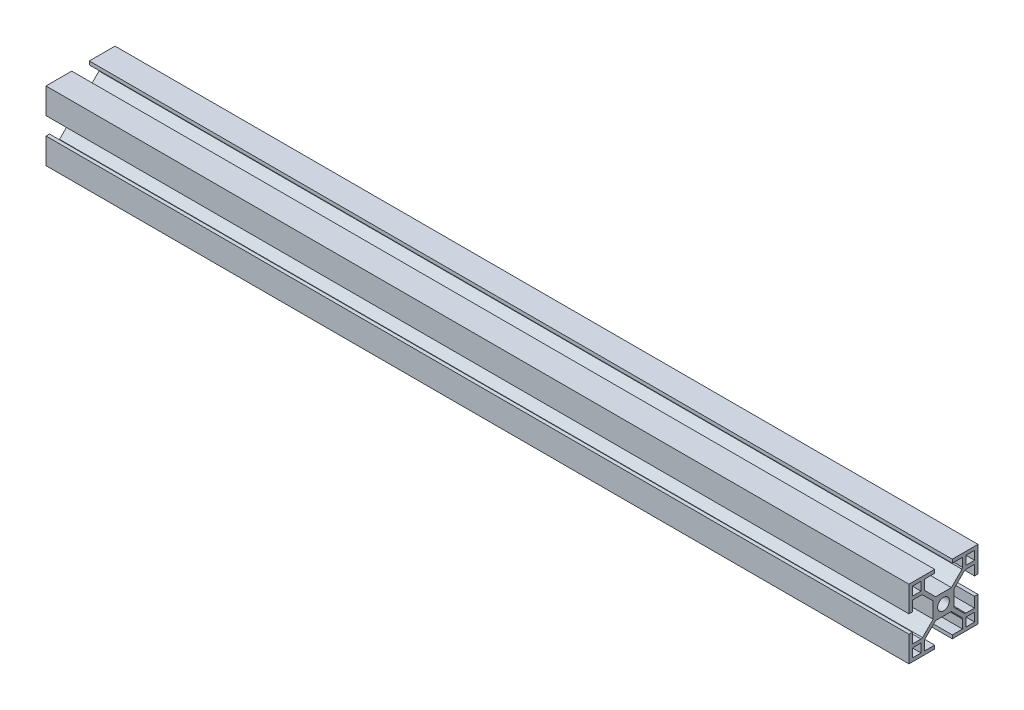
SolidWorks part; units mm, degrees
ref_plane "前视基准面" through (0, 0, 0) normal (0, 0, 1) x (1, 0, 0)
ref_plane "上视基准面" through (0, 0, 0) normal (0, 1, 0) x (1, 0, 0)
ref_plane "右视基准面" through (0, 0, 0) normal (1, 0, 0) x (0, 0, -1)
sketch "草图1" plane through (0, 0, 0) normal (1, 0, 0) x (0, 0, -1)
  line L0 (0, 0) -> (0, 6) construction
  line L5 (0, 6) -> (4.5858, 6)
  line L6 (6, 0) -> (6, -4.5858)
  line L10 (12.133, -10.7188) -> (6, -4.5858)
  line L11 (10.7188, 12.133) -> (4.5858, 6)
  line L12 (20, 20) -> (20, 5.1)
  line L18 (20, -20) -> (5.1, -20)
  line L22 (12.133, -10.7188) -> (13, -11)
  line L23 (18, -13) -> (18, -18)
  line L24 (18, -15.5) -> (18, -13)
  line L28 (18, -13) -> (13, -13)
  line L32 (13, -13) -> (13, -18)
  line L33 (18, -18) -> (13, -18)
  line L34 (11, -13) -> (11, -18)
  line L38 (11, -18) -> (5.1, -18)
  line L42 (10.7188, -12.133) -> (11, -13)
  line L43 (10.7188, -12.133) -> (4.5858, -6)
  line L44 (4.5858, -6) -> (0, -6)
  line L45 (10.7188, 12.133) -> (11, 13)
  line L46 (5.1, -18) -> (5.1, -20)
  line L47 (13, 18) -> (18, 18)
  line L49 (15.5, 18) -> (13, 18)
  line L56 (13, 18) -> (13, 13)
  line L59 (13, 13) -> (18, 13)
  line L60 (18, 18) -> (18, 13)
  line L61 (13, 11) -> (18, 11)
  line L62 (18, 11) -> (18, 5.1)
  line L63 (12.133, 10.7188) -> (13, 11)
  line L64 (12.133, 10.7188) -> (6, 4.5858)
  line L65 (6, 4.5858) -> (6, 0)
  line L66 (18, 5.1) -> (20, 5.1)
  line L67 (11, 18) -> (5.1, 18)
  line L68 (11, 13) -> (11, 18)
  line L69 (5.1, 18) -> (5.1, 20)
  line L70 (20, 20) -> (5.1, 20)
  line L71 (18, -11) -> (18, -5.1)
  line L72 (13, -11) -> (18, -11)
  line L73 (18, -5.1) -> (20, -5.1)
  line L74 (20, -20) -> (20, -5.1)
  line L75 (0, 0) -> (6, 0) construction
  line L76 (0, -6) -> (-4.5858, -6)
  line L77 (-10.7188, -12.133) -> (-4.5858, -6)
  line L78 (-20, -20) -> (-20, -5.1)
  line L79 (-10.7188, -12.133) -> (-11, -13)
  line L80 (-13, -18) -> (-18, -18)
  line L81 (-15.5, -18) -> (-13, -18)
  line L82 (-13, -18) -> (-13, -13)
  line L83 (-13, -13) -> (-18, -13)
  line L84 (-18, -18) -> (-18, -13)
  line L85 (-13, -11) -> (-18, -11)
  line L86 (-18, -11) -> (-18, -5.1)
  line L87 (-12.133, -10.7188) -> (-13, -11)
  line L88 (-12.133, -10.7188) -> (-6, -4.5858)
  line L89 (-6, -4.5858) -> (-6, 0)
  line L90 (-18, -5.1) -> (-20, -5.1)
  line L91 (-11, -18) -> (-5.1, -18)
  line L92 (-11, -13) -> (-11, -18)
  line L93 (-5.1, -18) -> (-5.1, -20)
  line L94 (-20, -20) -> (-5.1, -20)
  line L95 (0, 0) -> (0, -6) construction
  line L96 (-6, 0) -> (-6, 4.5858)
  line L97 (-12.133, 10.7188) -> (-6, 4.5858)
  line L98 (-20, 20) -> (-5.1, 20)
  line L99 (-12.133, 10.7188) -> (-13, 11)
  line L100 (-18, 13) -> (-18, 18)
  line L101 (-18, 15.5) -> (-18, 13)
  line L102 (-18, 13) -> (-13, 13)
  line L103 (-13, 13) -> (-13, 18)
  line L104 (-18, 18) -> (-13, 18)
  line L105 (-11, 13) -> (-11, 18)
  line L106 (-11, 18) -> (-5.1, 18)
  line L107 (-10.7188, 12.133) -> (-11, 13)
  line L108 (-10.7188, 12.133) -> (-4.5858, 6)
  line L109 (-4.5858, 6) -> (0, 6)
  line L110 (-5.1, 18) -> (-5.1, 20)
  line L111 (-18, 11) -> (-18, 5.1)
  line L112 (-13, 11) -> (-18, 11)
  line L113 (-18, 5.1) -> (-20, 5.1)
  line L114 (-20, 20) -> (-20, 5.1)
  line L115 (0, 0) -> (-6, 0) construction
  circle A0 centre (0, 0) radius 3.4
extrude "凸台-拉伸1" add sketch "草图1" along normal blind 500 contours L84 L80 L82 L83 | L33 L23 L28 L32 | L60 L47 L56 L59 | L12 L66 L62 L61 L63 L64 L65 L6 L10 L22 L72 L71 L73 L74 L18 L46 L38 L34 L42 L43 L44 L76 L77 L79 L92 L91 L93 L94 L78 L90 L86 L85 L87 L88 L89 L96 L97 L99 L112 L111 L113 L114 L98 L110 L106 L105 L107 L108 L109 L5 L11 L45 L68 L67 L69 L70 | A0 | L102 L103 L104 L100
sketch "草图3" plane through (0, 0, -20) normal (0, 0, -1) x (-1, 0, 0)
  line L0 (-250, 20) -> (-194, 20) construction
  line L5 (-250, 12.55) -> (-250, -20)
  line L6 (-500, -20) -> (0, -20) construction
  line L7 (-250, -20) -> (-250, 20)
  line L8 (-500, 20) -> (0, 20) construction
  line L9 (-192, 20) -> (-192, -20) construction
sketch "草图4" plane through (0, 0, 20) normal (0, 0, 1) x (1, 0, 0)
  line L1 (500, 20) -> (0, 20) construction
  line L2 (250, 20) -> (250, -20)
  line L3 (500, -20) -> (0, -20) construction
  line L4 (308, 20) -> (308, -20) construction
